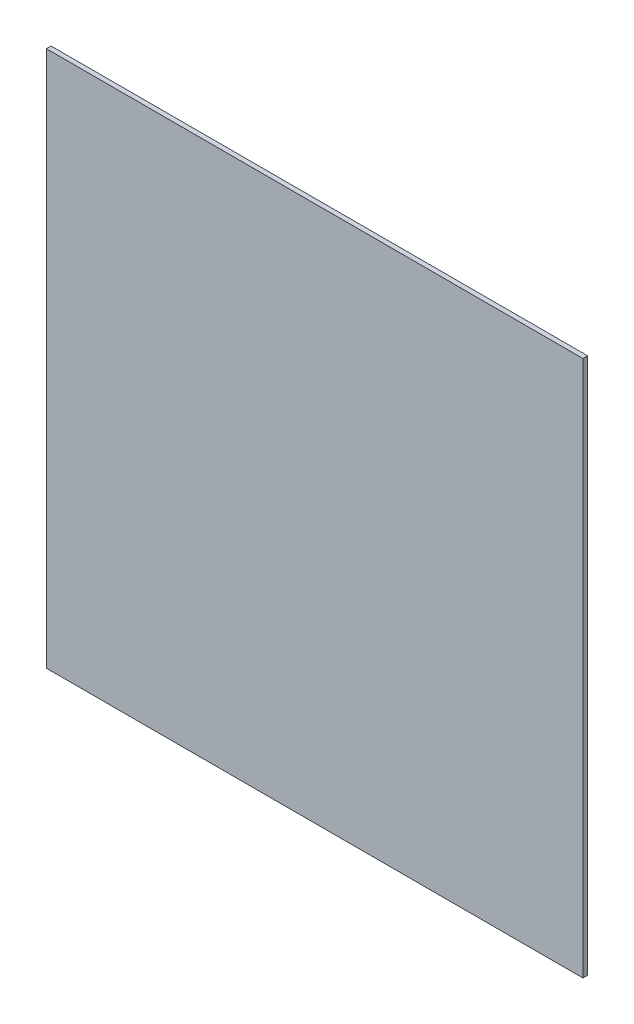
SolidWorks part; units mm, degrees
ref_plane "Front Plane" through (0, 0, 0) normal (0, 0, 1) x (1, 0, 0)
ref_plane "Top Plane" through (0, 0, 0) normal (0, 1, 0) x (1, 0, 0)
ref_plane "Right Plane" through (0, 0, 0) normal (1, 0, 0) x (0, 0, -1)
sketch "Sketch1" plane through (0, 0, 0) normal (0, 0, 1) x (1, 0, 0)
  line L1 (-68.65, -68.65) -> (68.65, -68.65)
  line L2 (-68.65, -68.65) -> (-68.65, 68.65)
  line L3 (-68.65, 68.65) -> (68.65, 68.65)
  line L4 (68.65, -68.65) -> (68.65, 68.65)
  line L5 (-68.65, -68.65) -> (68.65, 68.65) construction
  line L6 (-68.65, 68.65) -> (68.65, -68.65) construction
  point P0 (0, 0)
  dimension "D1" = 137.3
  dimension "D2" = 137.3
extrude "Boss-Extrude1" add sketch "Sketch1" along normal blind 1.2
sketch "Sketch2" plane through (0, 0, 0) normal (0, 0, -1) x (-1, 0, 0)
  line L1 (-67.5, -32.5) -> (67.5, -32.5) construction
  line L2 (-67.5, -32.5) -> (-67.5, 32.5) construction
  line L3 (-67.5, 32.5) -> (67.5, 32.5) construction
  line L4 (67.5, -32.5) -> (67.5, 32.5) construction
  line L5 (-67.5, -32.5) -> (67.5, 32.5) construction
  line L6 (-67.5, 32.5) -> (67.5, -32.5) construction
  point P0 (0, 0)
